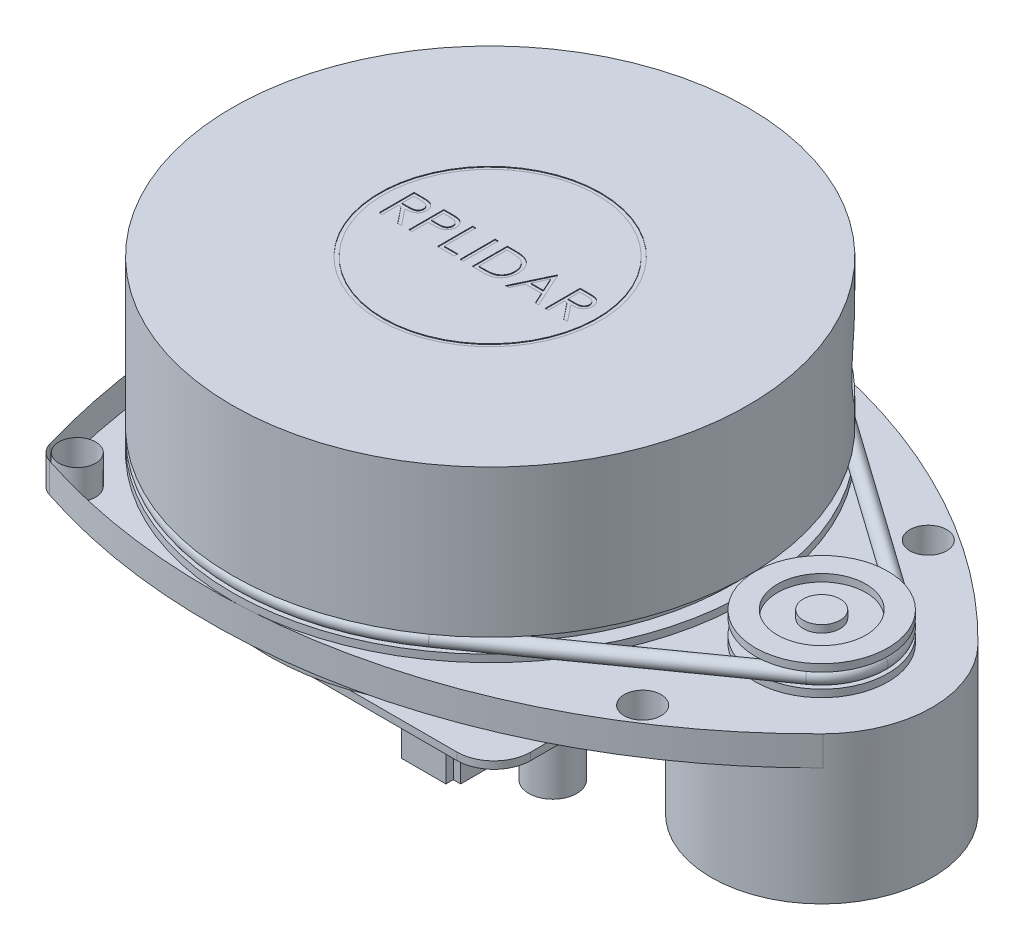
SolidWorks part; units mm, degrees
ref_plane "Front Plane" through (0, 0, 0) normal (0, 0, 1) x (1, 0, 0)
ref_plane "Top Plane" through (0, 0, 0) normal (0, 1, 0) x (1, 0, 0)
ref_plane "Right Plane" through (0, 0, 0) normal (1, 0, 0) x (0, 0, -1)
sketch "Sketch1" plane through (0, 0, 0) normal (0, 0, 1) x (1, 0, 0)
  line L0 (0, 67.5294) -> (0, -49.4672) construction
  line L1 (0, 0) -> (-35, 0)
  line L2 (38.6049, 0) -> (-38.6049, 0) construction
  line L3 (-35, 0) -> (-35, 1)
  line L4 (-35, 1) -> (-33, 1)
  line L5 (-33, 1) -> (-33, 3)
  line L6 (-33, 3) -> (-35, 3)
  line L7 (-35, 3) -> (-35, 23)
  line L8 (0, 23) -> (0, 0)
  line L9 (-15, 23) -> (-15, 22.9)
  line L10 (-15, 22.9) -> (-14.5, 22.9)
  line L11 (-14.5, 22.9) -> (-14.5, 23)
  line L12 (-35, 23) -> (-15, 23)
  line L13 (-14.5, 23) -> (0, 23)
  dimension "D1" = 1
  dimension "D2" = 2
  dimension "D3" = 2
  dimension "D4" = 35
  dimension "D5" = 2
  dimension "D6" = 23
  dimension "D7" = 0.1
  dimension "D8" = 0.5
  dimension "D9" = 14.5
revolve "Revolve2" add sketch "Sketch1" angle 360 about L0
sketch "Sketch2" plane through (0, 23, 0) normal (0, 1, 0) x (1, 0, 0)
  text T0 "RPLIDAR" font "Century Gothic" height in points 18
  dimension "D1" = 2.3813
extrude "Cut-Extrude2" cut sketch "Sketch2" against normal blind 0.1
sketch "Sketch3" plane through (0, 1, 0) normal (0, 1, 0) x (1, 0, 0)
  line L0 (-51.4402, 0) -> (173.1842, 0) construction
  line L1 (20.2222, 28.5668) -> (50.2, 7.3457)
  line L2 (50.2, -7.3457) -> (20.2222, -28.5668)
  circle A0 centre (0, 0) radius 35 construction
  arc A1 (20.2222, 28.5668) -> (20.2222, -28.5668) centre (0, 0) ccw
  arc A2 (50.2, -7.3457) -> (50.2, 7.3457) centre (45, 0) ccw
  circle A3 centre (0, 0) radius 35 construction
  dimension "D2" = 18
  dimension "D1" = 45
sketch "Sketch4" plane through (0, 0, 0) normal (0, 0, 1) x (1, 0, 0)
  line L0 (54, 2) -> (54, 1) construction
  line L1 (54, 1) -> (50.2, 1) construction
  line L3 (-51.4402, 1) -> (173.1842, 1) construction
  line L4 (54, 2) -> (53, 2) construction
  circle A0 centre (53, 2) radius 1
  point P5 (54, 1)
  dimension "D3" = 2
  dimension "D1" = 1
  dimension "D2" = 1
sweep "Sweep1" add profiles "Sketch4" path "Sketch3"
sketch "Sketch11" plane through (0, 0, 0) normal (0, 1, 0) x (1, 0, 0)
  circle A6 centre (45, 0) radius 9
  arc A7 (54, 0) -> (50.2, 7.3457) centre (45, 0) ccw construction
extrude "Boss-Extrude2" add sketch "Sketch11" along normal blind 1 separate body
sketch "Sketch12" plane through (0, 1, 0) normal (0, 1, 0) x (1, 0, 0)
  circle A0 centre (45, 0) radius 7
  arc A1 (52, 0) -> (49.0444, 5.7134) centre (45, 0) ccw construction
extrude "Boss-Extrude3" add sketch "Sketch12" along normal blind 2
sketch "Sketch13" plane through (0, 3, 0) normal (0, 1, 0) x (1, 0, 0)
  circle A0 centre (45, 0) radius 9
  arc A1 (54, 0) -> (50.2, 7.3457) centre (45, 0) ccw construction
extrude "Boss-Extrude4" add sketch "Sketch13" along normal blind 1
sketch "Sketch14" plane through (0, 4, 0) normal (0, 1, 0) x (1, 0, 0)
  circle A0 centre (45, 0) radius 2.5
  circle A1 centre (45, 0) radius 9 construction
  circle A2 centre (45, 0) radius 6
  dimension "D1" = 5
  dimension "D2" = 12
extrude "Cut-Extrude3" cut sketch "Sketch14" against normal blind 1 contours A2 | A0
sketch "Sketch15" plane through (0, 0, 0) normal (0, 0, 1) x (1, 0, 0)
  line L0 (0, 36.9072) -> (0, -30.0169) construction
  line L1 (13, 17) -> (26, 17)
  line L2 (-54.0593, 12) -> (73.8924, 12) construction
  line L3 (13, 7) -> (26, 7)
  circle A0 centre (-20, 12) radius 4
  arc A5 (13, 17) -> (13, 7) centre (19.5, 12) ccw
  arc A6 (26, 7) -> (26, 17) centre (19.5, 12) ccw
  dimension "D1" = 8
  dimension "D4" = 5
  dimension "D6" = 12
  dimension "D2" = 20
  dimension "D3" = 13
  dimension "D5" = 13
extrude "Cut-Extrude4" cut sketch "Sketch15" against normal through all
sketch "Sketch16" plane through (0, 0, 0) normal (0, -1, 0) x (1, 0, 0)
  line L0 (-102.0481, 0) -> (115.3971, 0) construction
  line L1 (-30.4056, -30.4056) -> (0, -30.4056) construction
  line L3 (0, 0) -> (-87.9139, 87.9139) construction
  line L4 (-30.4056, 30.4056) -> (0, 30.4056) construction
  line L5 (0, 0) -> (0, 138.2935) construction
  line L6 (-30.4056, 30.4056) -> (-30.4056, 0) construction
  circle A2 centre (0, 0) radius 35 construction
  arc A3 (55.6857, -10.5269) -> (55.6857, 10.5269) centre (45, 0) ccw
  circle A4 centre (45, 0) radius 9 construction
  arc A7 (55.6857, 10.5269) -> (-30.4056, 30.4056) centre (-3.0055, -47.2919) ccw
  arc A8 (-30.4056, 30.4056) -> (-30.4056, -30.4056) centre (67.9086, 0) ccw
  arc A9 (55.6857, -10.5269) -> (-30.4056, -30.4056) centre (-3.0055, 47.2919) cw
  dimension "D1" = 30
  dimension "D3" = 43
extrude "Boss-Extrude5" add sketch "Sketch16" along normal blind 4
sketch "Sketch18" plane through (0, -4, 0) normal (0, -1, 0) x (1, 0, 0)
  circle A0 centre (45, 0) radius 15
  arc A1 (55.6857, -10.5269) -> (55.6857, 10.5269) centre (45, 0) ccw construction
extrude "Boss-Extrude7" add sketch "Sketch18" along normal blind 16
sketch "Sketch19" plane through (0, -4, 0) normal (0, -1, 0) x (1, 0, 0)
  line L0 (0, 74.1504) -> (0, -76.1245) construction
  line L1 (-81.9972, 0) -> (97.5204, 0) construction
  arc A0 (29.8306, 3.184) -> (29.8306, -3.184) centre (0, 0) ccw
  arc A1 (29.8306, 3.184) -> (29.8306, -3.184) centre (45, 0) ccw
  circle A2 centre (45, 0) radius 15 construction
  dimension "D1" = 60
  dimension "D2" = 31
extrude "Boss-Extrude11" add sketch "Sketch19" along normal blind 5
sketch "Sketch20" plane through (0, -9, 0) normal (0, -1, 0) x (1, 0, 0)
  line L0 (29, 23.5) -> (29, -23.5)
  line L1 (24, 28.5) -> (-12, 28.5)
  line L2 (-17, 23.5) -> (-17, -23.5)
  line L3 (-12, -28.5) -> (24, -28.5)
  circle A0 centre (45, 0) radius 15 construction
  arc A1 (-17, -23.5) -> (-12, -28.5) centre (-12, -23.5) ccw
  arc A2 (29, -23.5) -> (24, -28.5) centre (24, -23.5) cw
  arc A3 (-12, 28.5) -> (-17, 23.5) centre (-12, 23.5) ccw
  arc A4 (29, 23.5) -> (24, 28.5) centre (24, 23.5) ccw
  point P10 (-17, -28.5)
  point P13 (29, -28.5)
  point P16 (-17, 28.5)
  dimension "D1" = 16
  dimension "D5" = 5
  dimension "D2" = 46
  dimension "D3" = 57
  dimension "D4" = 28.5
extrude "Boss-Extrude12" add sketch "Sketch20" along normal blind 1
fillet "Fillet1" radius 3 2 edges at (-30.4056, -2, 30.4056) (-30.4056, -2, -30.4056)
sketch "Sketch21" plane through (0, 0, 0) normal (0, 1, 0) x (1, 0, 0)
  line L0 (65.6031, 6.4654) -> (17.8155, 37.3454) construction
  line L1 (41.7093, 21.9054) -> (40.081, 19.3857) construction
  line L2 (-44.2011, 0) -> (-49.7046, 0) construction
  circle A0 centre (-27.977, 28.0657) radius 2.5
  arc A2 (-28.9206, 30.9134) -> (-30.8562, 28.9084) centre (-27.977, 28.0657) ccw construction
  circle A4 centre (40.081, 19.3857) radius 2.5
  arc A5 (55.6857, 10.5269) -> (2.2198, 34.9295) centre (-3.0055, -47.2919) ccw construction
  circle A8 centre (45, 0) radius 2.5
  circle A9 centre (45, 0) radius 2.5 construction
  circle A11 centre (-27.977, -28.0657) radius 2.5
  circle A12 centre (40.081, -19.3857) radius 2.5
  point P2 (-15.089, 39.817)
  point P3 (-51.305, 23.2289)
  point P10 (41.7093, 21.9054)
  point P11 (41.7717, 21.865)
  point P19 (0, 0)
  point P27 (0, 0)
  point P31 (0, 0)
  dimension "D1" = 5
  dimension "D2" = 5
  dimension "D3" = 0
  dimension "D4" = 3
  dimension "D5" = 20
extrude "Cut-Extrude6" cut sketch "Sketch21" against normal blind 10
sketch "Sketch22" plane through (0, -10, 0) normal (0, -1, 0) x (1, 0, 0)
  line L0 (26.5, 32.3083) -> (26.5, -14.2675) construction
  line L5 (29, -23.5) -> (29, 23.5) construction
  line L6 (-12, -28.5) -> (24, -28.5) construction
  line L7 (26.5, -22.5) -> (23, -22.5)
  line L8 (26.5, -22.5) -> (26.5, -14.5)
  line L9 (26.5, -14.5) -> (23, -14.5)
  line L10 (23, -22.5) -> (23, -14.5)
  line L11 (26.5, -12.5) -> (23, -12.5)
  line L12 (23, -12.5) -> (23, -3.5)
  line L13 (23, -3.5) -> (26.5, -3.5)
  line L14 (23, -60.1215) -> (23, -48.2932) construction
  line L15 (26.5, -3.5) -> (26.5, -12.5)
  line L17 (26.5, -1.5) -> (23, -1.5)
  line L18 (26.5, -1.5) -> (26.5, 8.5)
  line L19 (26.5, 8.5) -> (23, 8.5)
  line L20 (23, -1.5) -> (23, 8.5)
  dimension "D1" = 2.5
  dimension "D2" = 3.5
  dimension "D3" = 8
  dimension "D4" = 6
  dimension "D5" = 2
  dimension "D6" = 9
  dimension "D7" = 2
  dimension "D8" = 10
extrude "Boss-Extrude13" add sketch "Sketch22" along normal blind 6.5
sketch "Sketch23" plane through (0, -10, 0) normal (0, -1, 0) x (1, 0, 0)
  line L0 (24, 28.5) -> (-12, 28.5) construction
  line L1 (29, -23.5) -> (29, 23.5) construction
  circle A0 centre (24.75, 16.25) radius 3.25
  dimension "D1" = 6.5
  dimension "D2" = 12.25
  dimension "D3" = 4.25
extrude "Boss-Extrude14" add sketch "Sketch23" along normal blind 8
sketch "Sketch24" plane through (0, -10, 0) normal (0, -1, 0) x (1, 0, 0)
  line L0 (16, 27) -> (16, 28)
  line L1 (16, 28) -> (22, 28)
  line L2 (22, 28) -> (22, 27)
  line L3 (22, 27) -> (23, 27)
  line L4 (23, 27) -> (23, 21)
  line L5 (23, 21) -> (22, 21)
  line L6 (22, 21) -> (22, 20)
  line L7 (22, 20) -> (16, 20)
  line L8 (16, 20) -> (16, 21)
  line L9 (16, 21) -> (15, 21)
  line L10 (15, 21) -> (15, 27)
  line L11 (15, 27) -> (16, 27)
  line L12 (9.3675, 28.5) -> (-9.3675, 28.5) construction
  line L13 (29, -23.5) -> (29, 23.5) construction
  dimension "D1" = 0.5
  dimension "D2" = 6
  dimension "D3" = 1
  dimension "D4" = 6
extrude "Boss-Extrude15" add sketch "Sketch24" along normal blind 4
